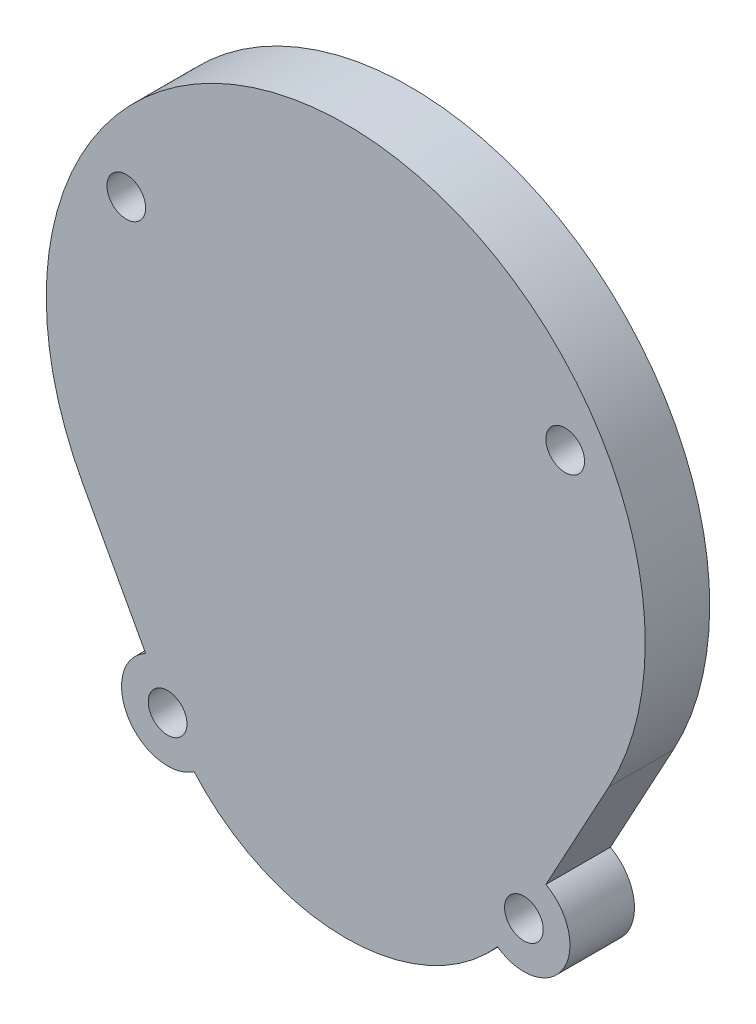
SolidWorks part; units mm, degrees
material "PET"
ref_plane "Front Plane" through (0, 0, 0) normal (0, 0, 1) x (1, 0, 0)
ref_plane "Top Plane" through (0, 0, 0) normal (0, 1, 0) x (1, 0, 0)
ref_plane "Right Plane" through (0, 0, 0) normal (1, 0, 0) x (0, 0, -1)
sketch "Sketch1" plane through (0, 0, 0) normal (0, 0, 1) x (1, 0, 0)
  line L0 (-28.5595, -15.5114) -> (-21.719, -28.1062)
  line L1 (28.5595, -15.5114) -> (21.719, -28.1062)
  line L2 (0, 0) -> (0, -22) construction
  line L3 (0, -22) -> (0, -44) construction
  line L6 (-23.8157, 13.75) -> (0, 0) construction
  line L7 (0, 0) -> (23.8157, 13.75) construction
  line L10 (-21.719, -28.1062) -> (-19.3326, -32.5) construction
  line L11 (21.719, -28.1062) -> (19.3326, -32.5) construction
  arc A0 (28.5595, -15.5114) -> (-28.5595, -15.5114) centre (0, 0) ccw
  arc A1 (-16.4624, -36.5941) -> (16.4624, -36.5941) centre (0, -22) ccw
  circle A5 centre (-23.8157, 13.75) radius 2.1
  circle A6 centre (23.8157, 13.75) radius 2.1
  arc A7 (-21.719, -28.1062) -> (-16.4624, -36.5941) centre (-19.3326, -32.5) ccw
  arc A8 (16.4624, -36.5941) -> (21.719, -28.1062) centre (19.3326, -32.5) ccw
  arc A9 (-19.3326, -32.5) -> (19.3326, -32.5) centre (0, -22) ccw construction
  circle A10 centre (-19.3326, -32.5) radius 2.1
  circle A11 centre (19.3326, -32.5) radius 2.1
  dimension "D1" = 65
  dimension "D2" = 22
  dimension "D3" = 44
  dimension "D4" = 10
  dimension "D5" = 4.2
  dimension "D6" = 4.2
  dimension "D7" = 10
  dimension "D10" = 5
  dimension "D11" = 5
  dimension "D12" = 4.2
  dimension "D13" = 4.2
  dimension "D8" = 120
  dimension "D9" = 120
extrude "Boss-Extrude1" add sketch "Sketch1" along normal blind 7
sketch "Sketch2" plane through (0, 0, 0) normal (0, 0, -1) x (-1, 0, 0)
  line L0 (-28.5595, -15.5114) -> (-19.3326, -32.5) construction
  line L3 (19.3326, -32.5) -> (28.5595, -15.5114) construction
  line L4 (-23.7264, -12.8864) -> (-14.4995, -29.875)
  line L7 (14.4995, -29.875) -> (23.7264, -12.8864)
  line L8 (-21.0901, -11.4545) -> (-11.8632, -28.4432)
  line L9 (-21.719, -28.1062) -> (-28.5595, -15.5114) construction
  line L10 (28.5595, -15.5114) -> (21.719, -28.1062) construction
  line L11 (11.8632, -28.4432) -> (21.0901, -11.4545)
  line L12 (-10.332, -34.8647) -> (1.0028, -47.1659) construction
  line L13 (4.4391, -48.3739) -> (14.4951, -29.883) construction
  line L14 (-8.2859, -32.6581) -> (2.9434, -44.8447) construction
  line L15 (2.9434, -44.8447) -> (11.8596, -28.4497) construction
  line L16 (-14.1176, -38.8729) -> (-3.0691, -50.8634) construction
  line L17 (8.3178, -52.7538) -> (19.3268, -32.5107) construction
  arc A0 (28.5595, -15.5114) -> (-28.5595, -15.5114) centre (0, 0) ccw construction
  arc A4 (23.7264, -12.8864) -> (24.327, 11.7132) centre (0, 0) ccw
  arc A6 (-14.4995, -29.875) -> (14.4995, -29.875) centre (0, -22) ccw
  arc A8 (21.0901, -11.4545) -> (-21.0901, -11.4545) centre (0, 0) ccw
  arc A10 (-11.8632, -28.4432) -> (-8.2859, -32.6581) centre (0, -22) ccw construction
  arc A12 (-24.327, 11.7132) -> (-22.3074, 15.2112) centre (-23.8157, 13.75) ccw
  arc A13 (22.3074, 15.2112) -> (24.327, 11.7132) centre (23.8157, 13.75) ccw
  arc A15 (-24.327, 11.7132) -> (-23.7264, -12.8864) centre (0, 0) ccw
  arc A16 (23.7264, -12.8864) -> (-23.7264, -12.8864) centre (0, 0) ccw construction
  arc A17 (22.3074, 15.2112) -> (-22.3074, 15.2112) centre (0, 0) ccw
  arc A18 (2.9434, -44.8447) -> (2.9434, -44.8447) centre (2.9434, -44.8447) ccw construction
  arc A19 (-14.4995, -29.875) -> (-10.332, -34.8647) centre (0, -22) ccw construction
  arc A20 (-19.3326, -32.5) -> (-14.1176, -38.8729) centre (0, -22) ccw construction
  arc A21 (-3.0691, -50.8634) -> (8.3178, -52.7538) centre (3.8084, -44.6764) ccw construction
  arc A22 (19.3268, -32.5107) -> (19.3326, -32.5) centre (0, -22) ccw construction
  circle A23 centre (0, -22) radius 22 construction
  arc A24 (-16.4624, -36.5941) -> (16.4624, -36.5941) centre (0, -22) ccw construction
  arc A25 (14.4951, -29.883) -> (14.4995, -29.875) centre (0, -22) ccw construction
  arc A26 (11.8596, -28.4497) -> (11.8632, -28.4432) centre (0, -22) ccw construction
  arc A27 (1.0028, -47.1659) -> (4.4391, -48.3739) centre (3.8084, -44.6764) ccw construction
  arc A28 (-11.8632, -28.4432) -> (11.8632, -28.4432) centre (0, -22) ccw
  dimension "D3" = 4.2
  dimension "D5" = 4.2
  dimension "D1" = 5.5
  dimension "D2" = 3
extrude "Boss-Extrude2" add sketch "Sketch2" along normal blind 2
sketch "Sketch3" plane through (0, 0, 0) normal (0, 0, -1) x (-1, 0, 0)
  circle A0 centre (0, -22) radius 7.05
  dimension "D1" = 14.1
extrude "Cut-Extrude1" cut sketch "Sketch3" against normal blind 5
sketch "Sketch4" plane through (0, 0, 0) normal (0, 0, -1) x (-1, 0, 0)
  circle A0 centre (0, 0) radius 7.5
  dimension "D1" = 15
extrude "Cut-Extrude2" cut sketch "Sketch4" against normal blind 2
